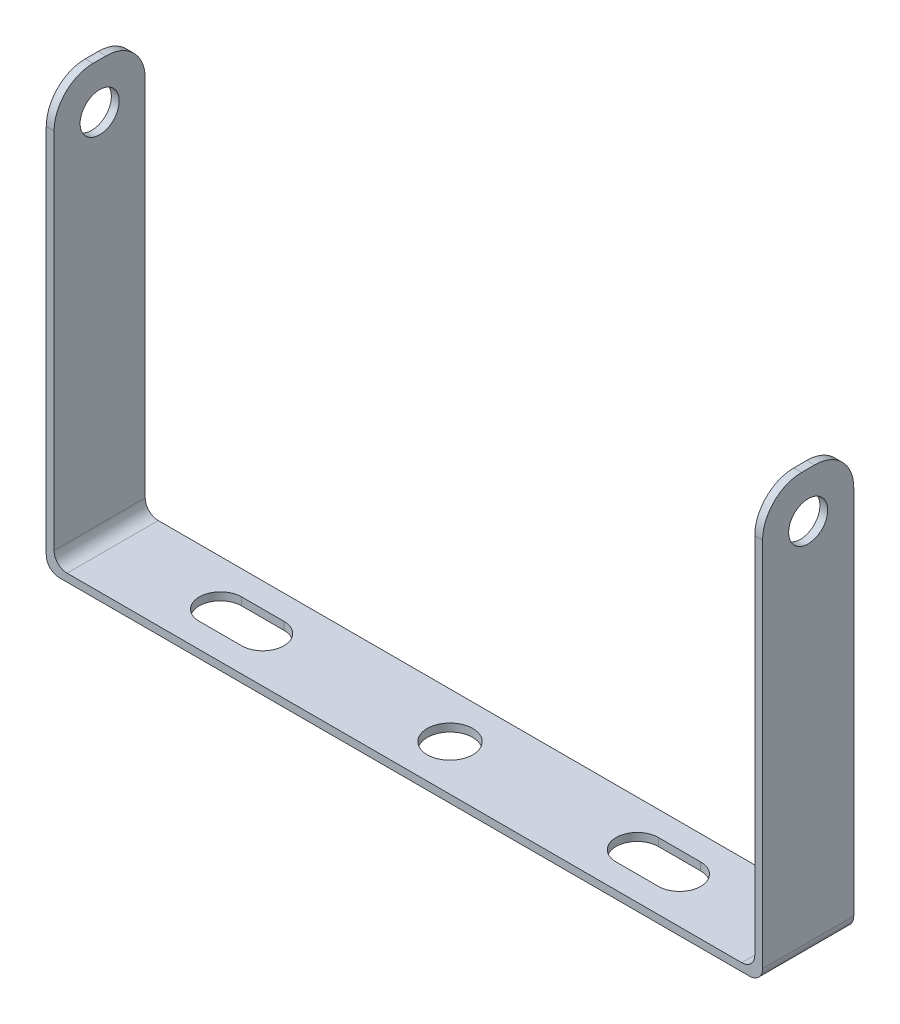
SolidWorks part; units mm, degrees
ref_plane "Ebene vorne" through (0, 0, 0) normal (0, 0, 1) x (1, 0, 0)
ref_plane "Ebene oben" through (0, 0, 0) normal (0, 1, 0) x (1, 0, 0)
ref_plane "Ebene rechts" through (0, 0, 0) normal (1, 0, 0) x (0, 0, -1)
sketch "Skizze1" plane through (0, 0, 0) normal (0, 0, 1) x (1, 0, 0)
  line L0 (0, 0) -> (-110, 0)
  line L1 (-110, 0) -> (-110, 65)
  line L2 (0, 0) -> (0, 65)
  line L3 (-1.2, 1.2) -> (-1.2, 65)
  line L4 (-1.2, 1.2) -> (-108.8, 1.2)
  line L5 (-108.8, 1.2) -> (-108.8, 65)
  line L6 (-110, 65) -> (-108.8, 65)
  line L7 (0, 65) -> (-1.2, 65)
  dimension "D1" = 110
  dimension "D2" = 65
  dimension "D3" = 1.2
extrude "Aufsatz-Linear austragen1" add sketch "Skizze1" along normal blind 14
fillet "Verrundung1" radius 2 4 edges at (-1.2, 1.2, 7) (0, 0, 7) (-110, 0, 7) (-108.8, 1.2, 7)
sketch "Skizze2" plane through (0, 0, 0) normal (1, 0, 0) x (0, 0, -1)
  line L0 (-7, 65) -> (-7, 0) construction
  line L1 (-14, 65) -> (0, 65) construction
  line L2 (0, 0) -> (-14, 0) construction
  circle A0 centre (-7, 58) radius 3
  dimension "D1" = 6
  dimension "D2" = 7
extrude "Schnitt-Linear austragen1" cut sketch "Skizze2" against normal through all
fillet "Verrundung2" radius 6 4 edges at (-0.6, 65, 0) (-0.6, 65, 14) (-109.4, 65, 0) (-109.4, 65, 14)
sketch "Skizze3" plane through (0, 0, 0) normal (0, -1, 0) x (-1, 0, 0)
  line L0 (55, -14) -> (55, 0) construction
  line L1 (108, -14) -> (2, -14) construction
  line L2 (108, 0) -> (2, 0) construction
  line L3 (110, -7) -> (0, -7) construction
  line L4 (110, 0) -> (110, -14) construction
  line L5 (0, -14) -> (0, 0) construction
  line L6 (90.25, -7) -> (83.75, -7) construction
  line L7 (90.25, -10.25) -> (83.75, -10.25)
  line L8 (90.25, -3.75) -> (83.75, -3.75)
  line L9 (19.75, -7) -> (26.25, -7) construction
  line L10 (19.75, -10.25) -> (26.25, -10.25)
  line L11 (19.75, -3.75) -> (26.25, -3.75)
  circle A0 centre (55, -7) radius 3.5
  arc A1 (90.25, -10.25) -> (90.25, -3.75) centre (90.25, -7) ccw
  arc A2 (83.75, -3.75) -> (83.75, -10.25) centre (83.75, -7) ccw
  arc A3 (19.75, -10.25) -> (19.75, -3.75) centre (19.75, -7) cw
  arc A4 (26.25, -3.75) -> (26.25, -10.25) centre (26.25, -7) cw
  point P16 (87, -7)
  point P21 (80.5, -7)
  point P24 (23, -7)
  dimension "D1" = 7
  dimension "D2" = 6.5
  dimension "D3" = 6.5
  dimension "D4" = 25.5
extrude "Schnitt-Linear austragen2" cut sketch "Skizze3" against normal through all
ref_plane "Ebene1" through (-55, 0, 0) normal (-1, 0, 0) x (0, 0, 1)
ref_plane "Ebene2" through (0, 0, 7) normal (0, 0, -1) x (-1, 0, 0)
